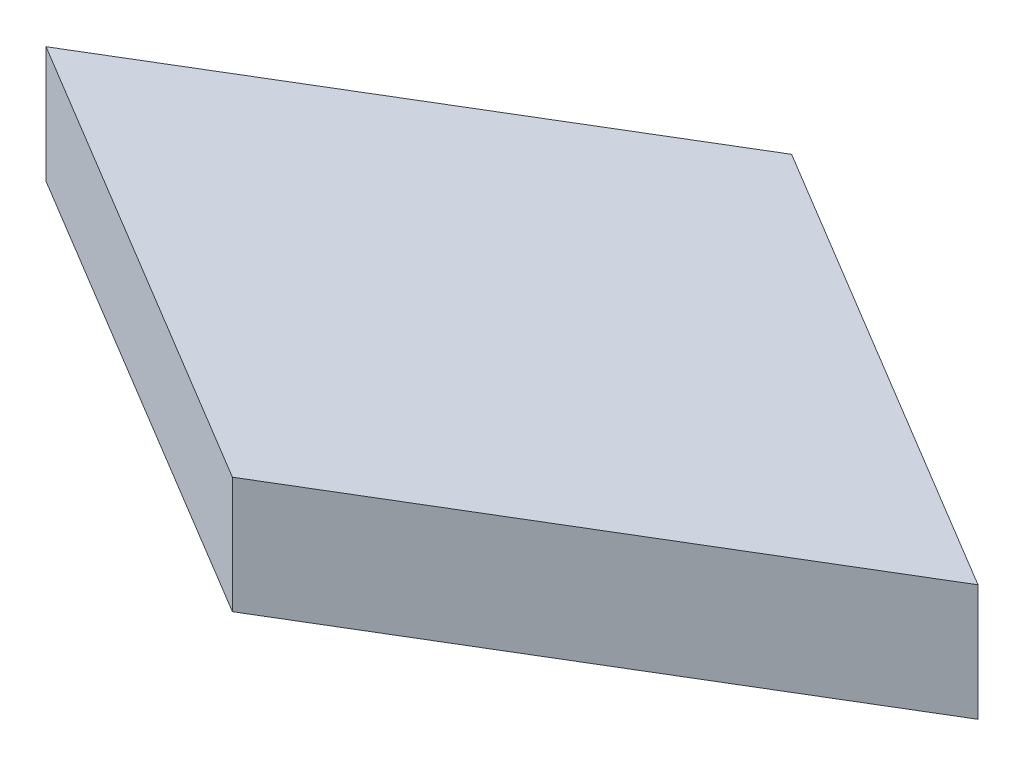
SolidWorks part; units mm, degrees
ref_plane "前视基准面" through (0, 0, 0) normal (0, 0, 1) x (1, 0, 0)
ref_plane "上视基准面" through (0, 0, 0) normal (0, 1, 0) x (1, 0, 0)
ref_plane "右视基准面" through (0, 0, 0) normal (1, 0, 0) x (0, 0, -1)
sketch "草图1" plane through (0, 0, 0) normal (0, 1, 0) x (1, 0, 0)
  line L0 (20, 0) -> (-20, 0) construction
  line L1 (0, 0) -> (0, -12) construction
  line L2 (0, -12) -> (-20, 0)
  line L3 (0, -12) -> (20, 0)
  line L4 (0, 12) -> (-20, 0)
  line L5 (0, 12) -> (20, 0)
  dimension "D1" = 20
  dimension "D2" = 12
extrude "凸台-拉伸1" add sketch "草图1" along normal blind 5
